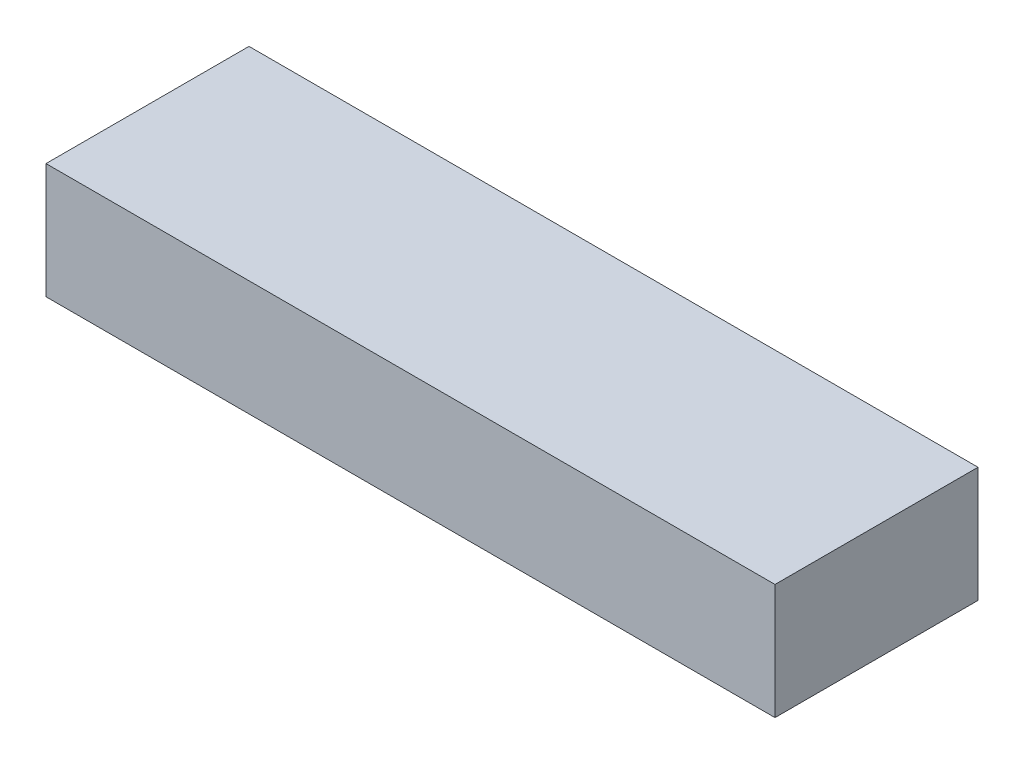
SolidWorks part; units mm, degrees
material "bateria avion"
ref_plane "Alzado" through (0, 0, 0) normal (0, 0, 1) x (1, 0, 0)
ref_plane "Planta" through (0, 0, 0) normal (0, 1, 0) x (1, 0, 0)
ref_plane "Vista lateral" through (0, 0, 0) normal (1, 0, 0) x (0, 0, -1)
sketch "Croquis1" plane through (0, 0, 0) normal (0, 1, 0) x (1, 0, 0)
  line L1 (-79, -22) -> (79, -22)
  line L2 (-79, -22) -> (-79, 22)
  line L3 (-79, 22) -> (79, 22)
  line L4 (79, -22) -> (79, 22)
  line L5 (-79, -22) -> (79, 22) construction
  line L6 (-79, 22) -> (79, -22) construction
  point P0 (0, 0)
  dimension "D1" = 44
  dimension "D2" = 158
extrude "Saliente-Extruir1" add sketch "Croquis1" along normal blind 25
